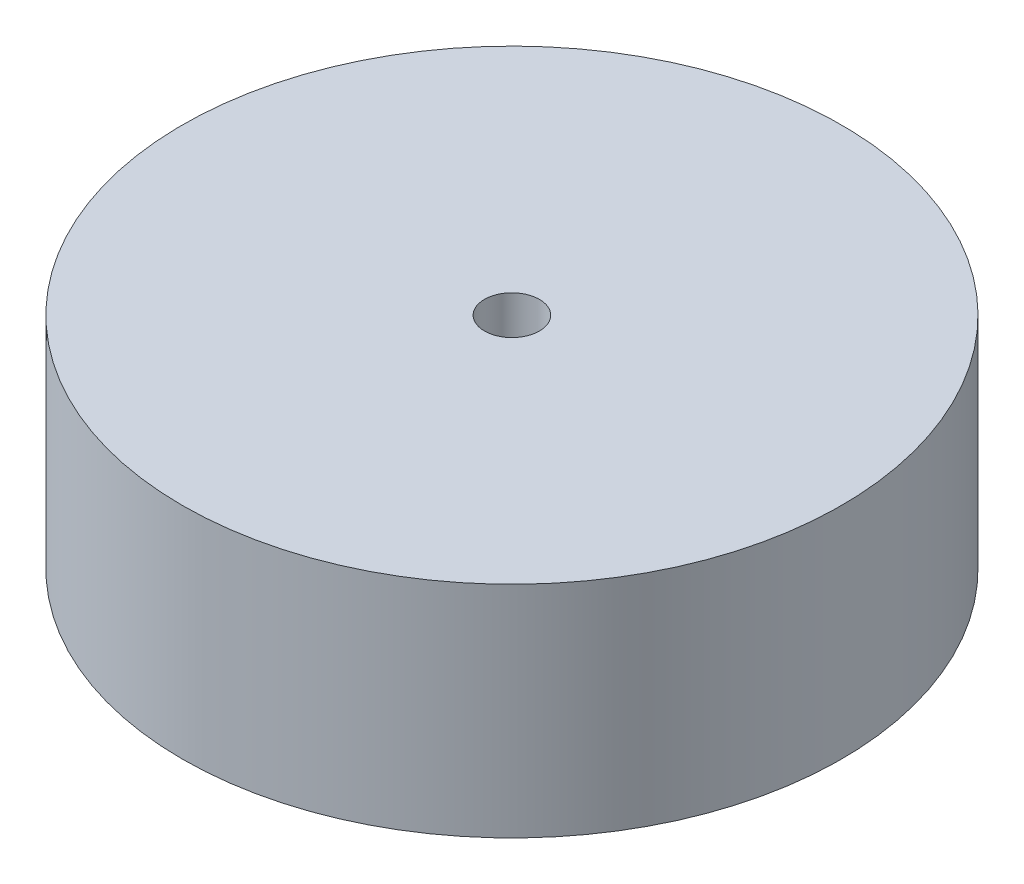
SolidWorks part; units mm, degrees
ref_plane "Front" through (0, 0, 0) normal (0, 0, 1) x (1, 0, 0)
ref_plane "Top" through (0, 0, 0) normal (0, 1, 0) x (1, 0, 0)
ref_plane "Right" through (0, 0, 0) normal (1, 0, 0) x (0, 0, -1)
sketch "Sketch1" plane through (0, 0, 0) normal (0, 1, 0) x (1, 0, 0)
  circle A0 centre (0, 0) radius 38.1
  circle A1 centre (0, 0) radius 3.175
  dimension "D1" = 76.2
  dimension "D2" = 6.35
extrude "Boss-Extrude1" add sketch "Sketch1" along normal blind 25.4
